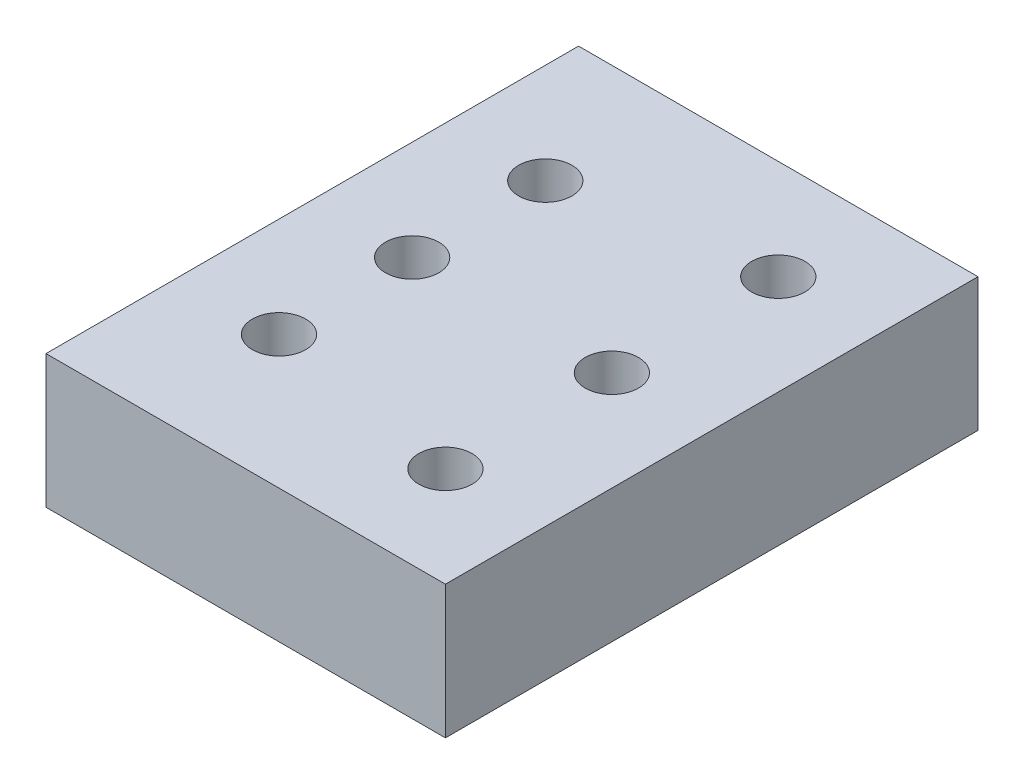
SolidWorks part; units mm, degrees
material "Acrylic (Medium-high impact)"
ref_plane "Front Plane" through (0, 0, 0) normal (0, 0, 1) x (1, 0, 0)
ref_plane "Top Plane" through (0, 0, 0) normal (0, 1, 0) x (1, 0, 0)
ref_plane "Right Plane" through (0, 0, 0) normal (1, 0, 0) x (0, 0, -1)
sketch "Sketch1" plane through (0, 0, 0) normal (0, 1, 0) x (1, 0, 0)
  line L5 (-15, 20) -> (15, 20)
  line L6 (-15, 20) -> (-15, -20)
  line L7 (-15, -20) -> (15, -20)
  line L8 (15, 20) -> (15, -20)
  circle A0 centre (7.5, 12.5) radius 2
  circle A2 centre (7.5, -12.5) radius 2
  circle A3 centre (-7.5, -10) radius 2
  circle A5 centre (-7.5, 10) radius 2
  circle A6 centre (-7.5, 0) radius 2
  circle A7 centre (7.5, 0) radius 2
  dimension "D5" = 4
  dimension "D6" = 10
  dimension "D7" = 4
  dimension "D8" = 4
  dimension "D9" = 7.5
  dimension "D10" = 4
  dimension "D12" = 7.5
  dimension "D18" = 12.5
  dimension "D1" = 40
  dimension "D2" = 30
  dimension "D3" = 20
  dimension "D4" = 15
  dimension "D11" = 7.5
  dimension "D13" = 7.5
  dimension "D14" = 7.5
  dimension "D15" = 10
  dimension "D16" = 7.5
  dimension "D17" = 10
  dimension "D20" = 7.5
extrude "Boss-Extrude1" add sketch "Sketch1" along normal blind 10
